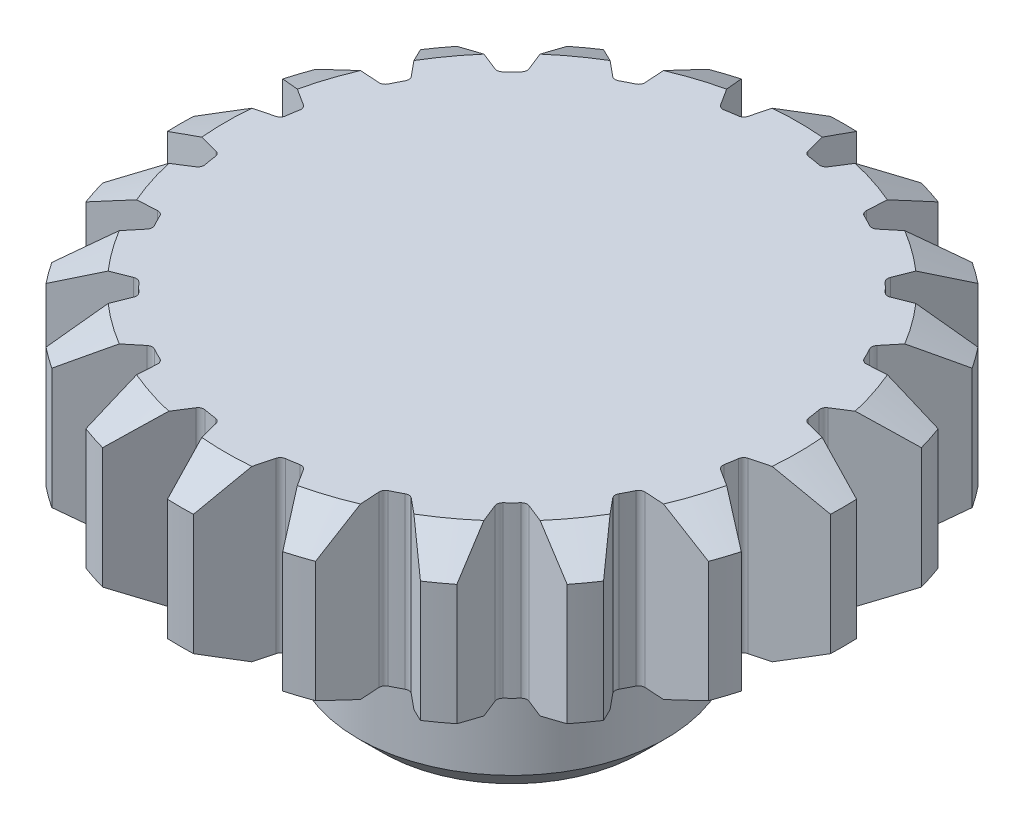
SolidWorks part; units mm, degrees
ref_plane "前视基准面" through (0, 0, 0) normal (0, 0, 1) x (1, 0, 0)
ref_plane "上视基准面" through (0, 0, 0) normal (0, 1, 0) x (1, 0, 0)
ref_plane "右视基准面" through (0, 0, 0) normal (1, 0, 0) x (0, 0, -1)
other "Configuration Table"
sketch "草图1" plane through (0, 0, 0) normal (0, 1, 0) x (1, 0, 0)
  line L0 (0.9745, 8.6442) -> (0.4232, 10.7717)
  line L1 (-0.4232, 10.7717) -> (-0.9745, 8.6442)
  line L2 (-1.7444, 8.5223) -> (-2.9261, 10.3753)
  line L3 (-3.7311, 10.1137) -> (-3.5981, 7.92)
  line L4 (-4.2925, 7.5661) -> (-5.989, 8.9632)
  line L5 (-6.6738, 8.4657) -> (-5.8694, 6.4205)
  line L6 (-6.4205, 5.8694) -> (-8.4657, 6.6738)
  line L7 (-8.9632, 5.989) -> (-7.5661, 4.2925)
  line L8 (-7.92, 3.5981) -> (-10.1137, 3.7311)
  line L9 (-10.3753, 2.9261) -> (-8.5223, 1.7444)
  line L10 (-8.6442, 0.9745) -> (-10.7717, 0.4232)
  line L11 (-10.7717, -0.4232) -> (-8.6442, -0.9745)
  line L12 (-8.5223, -1.7444) -> (-10.3753, -2.9261)
  line L13 (-10.1137, -3.7311) -> (-7.92, -3.5981)
  line L14 (-7.5661, -4.2925) -> (-8.9632, -5.989)
  line L15 (-8.4657, -6.6738) -> (-6.4205, -5.8694)
  line L16 (-5.8694, -6.4205) -> (-6.6738, -8.4657)
  line L17 (-5.989, -8.9632) -> (-4.2925, -7.5661)
  line L18 (-3.5981, -7.92) -> (-3.7311, -10.1137)
  line L19 (-2.9261, -10.3753) -> (-1.7444, -8.5223)
  line L20 (-0.9745, -8.6442) -> (-0.4232, -10.7717)
  line L21 (0.4232, -10.7717) -> (0.9745, -8.6442)
  line L22 (1.7444, -8.5223) -> (2.9261, -10.3753)
  line L23 (3.7311, -10.1137) -> (3.5981, -7.92)
  line L24 (4.2925, -7.5661) -> (5.989, -8.9632)
  line L25 (6.6738, -8.4657) -> (5.8694, -6.4205)
  line L26 (6.4205, -5.8694) -> (8.4657, -6.6738)
  line L27 (8.9632, -5.989) -> (7.5661, -4.2925)
  line L28 (7.92, -3.5981) -> (10.1137, -3.7311)
  line L29 (10.3753, -2.9261) -> (8.5223, -1.7444)
  line L30 (8.6442, -0.9745) -> (10.7717, -0.4232)
  line L31 (10.7717, 0.4232) -> (8.6442, 0.9745)
  line L32 (8.5223, 1.7444) -> (10.3753, 2.9261)
  line L33 (10.1137, 3.7311) -> (7.92, 3.5981)
  line L34 (7.5661, 4.2925) -> (8.9632, 5.989)
  line L35 (8.4657, 6.6738) -> (6.4205, 5.8694)
  line L36 (5.8694, 6.4205) -> (6.6738, 8.4657)
  line L37 (5.989, 8.9632) -> (4.2925, 7.5661)
  line L38 (3.5981, 7.92) -> (3.7311, 10.1137)
  line L39 (2.9261, 10.3753) -> (1.7444, 8.5223)
  arc A0 (0.4232, 10.7717) -> (-0.4232, 10.7717) centre (0, 0) ccw
  arc A1 (-1.1383, 8.4991) -> (-0.9745, 8.6442) centre (-1.1643, 8.6934) ccw
  arc A2 (-1.1383, 8.4991) -> (-1.5438, 8.4349) centre (0, 0) ccw
  arc A3 (-1.7444, 8.5223) -> (-1.5438, 8.4349) centre (-1.5791, 8.6277) ccw
  arc A4 (-2.9261, 10.3753) -> (-3.7311, 10.1137) centre (0, 0) ccw
  arc A5 (-3.7089, 7.7314) -> (-3.5981, 7.92) centre (-3.7937, 7.9081) ccw
  arc A6 (-3.7089, 7.7314) -> (-4.0748, 7.545) centre (0, 0) ccw
  arc A7 (-4.2925, 7.5661) -> (-4.0748, 7.545) centre (-4.1679, 7.7174) ccw
  arc A8 (-5.989, 8.9632) -> (-6.6738, 8.4657) centre (0, 0) ccw
  arc A9 (-5.9165, 6.2069) -> (-5.8694, 6.4205) centre (-6.0518, 6.3487) ccw
  arc A10 (-5.9165, 6.2069) -> (-6.2069, 5.9165) centre (0, 0) ccw
  arc A11 (-6.4205, 5.8694) -> (-6.2069, 5.9165) centre (-6.3487, 6.0518) ccw
  arc A12 (-8.4657, 6.6738) -> (-8.9632, 5.989) centre (0, 0) ccw
  arc A13 (-7.545, 4.0748) -> (-7.5661, 4.2925) centre (-7.7174, 4.1679) ccw
  arc A14 (-7.545, 4.0748) -> (-7.7314, 3.7089) centre (0, 0) ccw
  arc A15 (-7.92, 3.5981) -> (-7.7314, 3.7089) centre (-7.9081, 3.7937) ccw
  arc A16 (-10.1137, 3.7311) -> (-10.3753, 2.9261) centre (0, 0) ccw
  arc A17 (-8.4349, 1.5438) -> (-8.5223, 1.7444) centre (-8.6277, 1.5791) ccw
  arc A18 (-8.4349, 1.5438) -> (-8.4991, 1.1383) centre (0, 0) ccw
  arc A19 (-8.6442, 0.9745) -> (-8.4991, 1.1383) centre (-8.6934, 1.1643) ccw
  arc A20 (-10.7717, 0.4232) -> (-10.7717, -0.4232) centre (0, 0) ccw
  arc A21 (-8.4991, -1.1383) -> (-8.6442, -0.9745) centre (-8.6934, -1.1643) ccw
  arc A22 (-8.4991, -1.1383) -> (-8.4349, -1.5438) centre (0, 0) ccw
  arc A23 (-8.5223, -1.7444) -> (-8.4349, -1.5438) centre (-8.6277, -1.5791) ccw
  arc A24 (-10.3753, -2.9261) -> (-10.1137, -3.7311) centre (0, 0) ccw
  arc A25 (-7.7314, -3.7089) -> (-7.92, -3.5981) centre (-7.9081, -3.7937) ccw
  arc A26 (-7.7314, -3.7089) -> (-7.545, -4.0748) centre (0, 0) ccw
  arc A27 (-7.5661, -4.2925) -> (-7.545, -4.0748) centre (-7.7174, -4.1679) ccw
  arc A28 (-8.9632, -5.989) -> (-8.4657, -6.6738) centre (0, 0) ccw
  arc A29 (-6.2069, -5.9165) -> (-6.4205, -5.8694) centre (-6.3487, -6.0518) ccw
  arc A30 (-6.2069, -5.9165) -> (-5.9165, -6.2069) centre (0, 0) ccw
  arc A31 (-5.8694, -6.4205) -> (-5.9165, -6.2069) centre (-6.0518, -6.3487) ccw
  arc A32 (-6.6738, -8.4657) -> (-5.989, -8.9632) centre (0, 0) ccw
  arc A33 (-4.0748, -7.545) -> (-4.2925, -7.5661) centre (-4.1679, -7.7174) ccw
  arc A34 (-4.0748, -7.545) -> (-3.7089, -7.7314) centre (0, 0) ccw
  arc A35 (-3.5981, -7.92) -> (-3.7089, -7.7314) centre (-3.7937, -7.9081) ccw
  arc A36 (-3.7311, -10.1137) -> (-2.9261, -10.3753) centre (0, 0) ccw
  arc A37 (-1.5438, -8.4349) -> (-1.7444, -8.5223) centre (-1.5791, -8.6277) ccw
  arc A38 (-1.5438, -8.4349) -> (-1.1383, -8.4991) centre (0, 0) ccw
  arc A39 (-0.9745, -8.6442) -> (-1.1383, -8.4991) centre (-1.1643, -8.6934) ccw
  arc A40 (-0.4232, -10.7717) -> (0.4232, -10.7717) centre (0, 0) ccw
  arc A41 (1.1383, -8.4991) -> (0.9745, -8.6442) centre (1.1643, -8.6934) ccw
  arc A42 (1.1383, -8.4991) -> (1.5438, -8.4349) centre (0, 0) ccw
  arc A43 (1.7444, -8.5223) -> (1.5438, -8.4349) centre (1.5791, -8.6277) ccw
  arc A44 (2.9261, -10.3753) -> (3.7311, -10.1137) centre (0, 0) ccw
  arc A45 (3.7089, -7.7314) -> (3.5981, -7.92) centre (3.7937, -7.9081) ccw
  arc A46 (3.7089, -7.7314) -> (4.0748, -7.545) centre (0, 0) ccw
  arc A47 (4.2925, -7.5661) -> (4.0748, -7.545) centre (4.1679, -7.7174) ccw
  arc A48 (5.989, -8.9632) -> (6.6738, -8.4657) centre (0, 0) ccw
  arc A49 (5.9165, -6.2069) -> (5.8694, -6.4205) centre (6.0518, -6.3487) ccw
  arc A50 (5.9165, -6.2069) -> (6.2069, -5.9165) centre (0, 0) ccw
  arc A51 (6.4205, -5.8694) -> (6.2069, -5.9165) centre (6.3487, -6.0518) ccw
  arc A52 (8.4657, -6.6738) -> (8.9632, -5.989) centre (0, 0) ccw
  arc A53 (7.545, -4.0748) -> (7.5661, -4.2925) centre (7.7174, -4.1679) ccw
  arc A54 (7.545, -4.0748) -> (7.7314, -3.7089) centre (0, 0) ccw
  arc A55 (7.92, -3.5981) -> (7.7314, -3.7089) centre (7.9081, -3.7937) ccw
  arc A56 (10.1137, -3.7311) -> (10.3753, -2.9261) centre (0, 0) ccw
  arc A57 (8.4349, -1.5438) -> (8.5223, -1.7444) centre (8.6277, -1.5791) ccw
  arc A58 (8.4349, -1.5438) -> (8.4991, -1.1383) centre (0, 0) ccw
  arc A59 (8.6442, -0.9745) -> (8.4991, -1.1383) centre (8.6934, -1.1643) ccw
  arc A60 (10.7717, -0.4232) -> (10.7717, 0.4232) centre (0, 0) ccw
  arc A61 (8.4991, 1.1383) -> (8.6442, 0.9745) centre (8.6934, 1.1643) ccw
  arc A62 (8.4991, 1.1383) -> (8.4349, 1.5438) centre (0, 0) ccw
  arc A63 (8.5223, 1.7444) -> (8.4349, 1.5438) centre (8.6277, 1.5791) ccw
  arc A64 (10.3753, 2.9261) -> (10.1137, 3.7311) centre (0, 0) ccw
  arc A65 (7.7314, 3.7089) -> (7.92, 3.5981) centre (7.9081, 3.7937) ccw
  arc A66 (7.7314, 3.7089) -> (7.545, 4.0748) centre (0, 0) ccw
  arc A67 (7.5661, 4.2925) -> (7.545, 4.0748) centre (7.7174, 4.1679) ccw
  arc A68 (8.9632, 5.989) -> (8.4657, 6.6738) centre (0, 0) ccw
  arc A69 (6.2069, 5.9165) -> (6.4205, 5.8694) centre (6.3487, 6.0518) ccw
  arc A70 (6.2069, 5.9165) -> (5.9165, 6.2069) centre (0, 0) ccw
  arc A71 (5.8694, 6.4205) -> (5.9165, 6.2069) centre (6.0518, 6.3487) ccw
  arc A72 (6.6738, 8.4657) -> (5.989, 8.9632) centre (0, 0) ccw
  arc A73 (4.0748, 7.545) -> (4.2925, 7.5661) centre (4.1679, 7.7174) ccw
  arc A74 (4.0748, 7.545) -> (3.7089, 7.7314) centre (0, 0) ccw
  arc A75 (3.5981, 7.92) -> (3.7089, 7.7314) centre (3.7937, 7.9081) ccw
  arc A76 (3.7311, 10.1137) -> (2.9261, 10.3753) centre (0, 0) ccw
  arc A77 (1.5438, 8.4349) -> (1.7444, 8.5223) centre (1.5791, 8.6277) ccw
  arc A78 (1.5438, 8.4349) -> (1.1383, 8.4991) centre (0, 0) ccw
  arc A79 (0.9745, 8.6442) -> (1.1383, 8.4991) centre (1.1643, 8.6934) ccw
extrude "凸台-拉伸1" add sketch "草图1" along normal blind 5.5
sketch "草图3" plane through (0, 0, 0) normal (0, -1, 0) x (1, 0, 0)
  arc A0 (-0.7265, 3.1784) -> (-0.8949, 3.1351) centre (-0.0001, -0.0002) ccw
  arc A1 (-0.99, 2.5302) -> (-1.0107, 2.522) centre (-0.0002, -0.0001) ccw
  arc A2 (-1.4941, 2.8979) -> (-1.6465, 2.8141) centre (-0.0001, -0.0002) ccw
  arc A3 (-1.5881, 2.2045) -> (-1.6062, 2.1914) centre (-0.0002, -0.0001) ccw
  arc A4 (-2.1679, 2.4353) -> (-2.2946, 2.3163) centre (0, -0.0002) ccw
  arc A5 (-2.0865, 1.7404) -> (-2.1007, 1.7232) centre (-0.0002, -0.0001) ccw
  arc A6 (-2.7054, 1.8197) -> (-2.7986, 1.6729) centre (0, -0.0002) ccw
  arc A7 (-2.4538, 1.1669) -> (-2.4633, 1.1467) centre (-0.0002, -0.0001) ccw
  arc A8 (-3.073, 1.0897) -> (-3.1267, 0.9244) centre (0, -0.0001) ccw
  arc A9 (-2.6669, 0.52) -> (-2.6711, 0.4981) centre (-0.0002, -0.0001) ccw
  arc A10 (-3.2475, 0.2913) -> (-3.2584, 0.1178) centre (0, -0.0001) ccw
  arc A11 (-2.7124, -0.1595) -> (-2.711, -0.1818) centre (-0.0002, -0.0001) ccw
  arc A12 (-3.2179, -0.5254) -> (-3.1853, -0.6961) centre (0, 0) ccw
  arc A13 (-2.5876, -0.829) -> (-2.5807, -0.8502) centre (-0.0002, -0.0001) ccw
  arc A14 (-2.9862, -1.3091) -> (-2.9122, -1.4664) centre (0, 0) ccw
  arc A15 (-2.3001, -1.4464) -> (-2.2882, -1.4653) centre (-0.0002, -0.0001) ccw
  arc A16 (-2.5668, -2.0106) -> (-2.456, -2.1445) centre (0, 0.0001) ccw
  arc A17 (-1.8682, -1.973) -> (-1.8519, -1.9883) centre (-0.0002, -0.0001) ccw
  arc A18 (-1.9862, -2.5857) -> (-1.8456, -2.6879) centre (0, 0.0001) ccw
  arc A19 (-1.3188, -2.3756) -> (-1.2993, -2.3863) centre (-0.0002, -0.0001) ccw
  arc A20 (-1.2808, -2.9984) -> (-1.1191, -3.0624) centre (-0.0001, 0.0001) ccw
  arc A21 (-0.6866, -2.6289) -> (-0.665, -2.6344) centre (-0.0002, -0.0001) ccw
  arc A22 (-0.4949, -3.2227) -> (-0.3224, -3.2444) centre (-0.0001, 0.0001) ccw
  arc A23 (-0.0114, -2.717) -> (0.011, -2.717) centre (-0.0002, -0.0001) ccw
  arc A24 (0.3221, -3.2444) -> (0.4945, -3.2227) centre (-0.0002, 0.0001) ccw
  arc A25 (0.6647, -2.6344) -> (0.6863, -2.6289) centre (-0.0002, -0.0001) ccw
  arc A26 (1.1188, -3.0624) -> (1.2804, -2.9984) centre (-0.0002, 0.0001) ccw
  arc A27 (1.299, -2.3863) -> (1.3185, -2.3756) centre (-0.0002, -0.0001) ccw
  arc A28 (1.8452, -2.6879) -> (1.9859, -2.5857) centre (-0.0003, 0.0001) ccw
  arc A29 (1.8516, -1.9883) -> (1.8678, -1.973) centre (-0.0002, -0.0001) ccw
  arc A30 (2.4557, -2.1445) -> (2.5665, -2.0106) centre (-0.0003, 0.0001) ccw
  arc A31 (2.2878, -1.4653) -> (2.2998, -1.4464) centre (-0.0002, -0.0001) ccw
  arc A32 (2.9118, -1.4664) -> (2.9858, -1.3091) centre (-0.0003, 0) ccw
  arc A33 (2.5803, -0.8502) -> (2.5872, -0.829) centre (-0.0002, -0.0001) ccw
  arc A34 (3.185, -0.6961) -> (3.2176, -0.5254) centre (-0.0004, 0) ccw
  arc A35 (2.7107, -0.1818) -> (2.7121, -0.1595) centre (-0.0002, -0.0001) ccw
  arc A36 (3.2581, 0.1178) -> (3.2471, 0.2913) centre (-0.0004, -0.0001) ccw
  arc A37 (2.6707, 0.4981) -> (2.6666, 0.52) centre (-0.0002, -0.0001) ccw
  arc A38 (3.1264, 0.9244) -> (3.0727, 1.0897) centre (-0.0003, -0.0001) ccw
  arc A39 (2.4629, 1.1467) -> (2.4534, 1.1669) centre (-0.0002, -0.0001) ccw
  arc A40 (2.7982, 1.6729) -> (2.7051, 1.8197) centre (-0.0003, -0.0002) ccw
  arc A41 (2.1004, 1.7232) -> (2.0862, 1.7404) centre (-0.0002, -0.0001) ccw
  arc A42 (2.2943, 2.3163) -> (2.1676, 2.4353) centre (-0.0003, -0.0002) ccw
  arc A43 (1.6058, 2.1914) -> (1.5878, 2.2045) centre (-0.0002, -0.0001) ccw
  arc A44 (1.6461, 2.8141) -> (1.4938, 2.8979) centre (-0.0003, -0.0002) ccw
  arc A45 (1.0104, 2.522) -> (0.9896, 2.5302) centre (-0.0002, -0.0001) ccw
  arc A46 (0.8945, 3.1351) -> (0.7262, 3.1784) centre (-0.0002, -0.0002) ccw
  arc A47 (0.3514, 2.6941) -> (0.3293, 2.6969) centre (-0.0002, -0.0001) ccw
  arc A48 (0.0867, 3.2591) -> (-0.0871, 3.2591) centre (-0.0002, -0.0003) ccw
  arc A49 (-0.3296, 2.6969) -> (-0.3518, 2.6941) centre (-0.0002, -0.0001) ccw
  circle A51 centre (0, -0.0001) radius 5
  spline S0 degree 3 poles (-0.3518, 2.6941) (-0.3605, 2.6929) (-0.3784, 2.6931) (-0.4128, 2.7028) (-0.4491, 2.7298) (-0.4793, 2.7741) (-0.4985, 2.8237) (-0.5171, 2.8734) (-0.5482, 2.937) (-0.6123, 3.0431) (-0.6788, 3.1261) (-0.7265, 3.1784) knots 0 0 0 0 0.041734 0.083468 0.166936 0.250403 0.333871 0.417137 0.500403 0.666936 1 1 1 1 weights 1 1 1 1 1 1 1 1 1 1 1 1
  spline S1 degree 3 poles (-0.8949, 3.1351) (-0.9115, 3.0664) (-0.9298, 2.9616) (-0.9349, 2.8377) (-0.9315, 2.7671) (-0.9238, 2.7145) (-0.9168, 2.6618) (-0.9219, 2.6084) (-0.9407, 2.5673) (-0.9661, 2.5422) (-0.9817, 2.5334) (-0.99, 2.5302) knots 0 0 0 0 0.333125 0.499688 0.582969 0.66625 0.749687 0.833125 0.916562 0.958281 1 1 1 1 weights 1 1 1 1 1 1 1 1 1 1 1 1
  spline S2 degree 3 poles (-1.0107, 2.522) (-1.0189, 2.5187) (-1.0363, 2.5144) (-1.072, 2.5153) (-1.1139, 2.5324) (-1.1541, 2.5678) (-1.1851, 2.6111) (-1.2155, 2.6546) (-1.2614, 2.7085) (-1.3499, 2.7953) (-1.4349, 2.8591) (-1.4941, 2.8979) knots 0 0 0 0 0.041734 0.083468 0.166936 0.250403 0.333871 0.417137 0.500403 0.666936 1 1 1 1 weights 1 1 1 1 1 1 1 1 1 1 1 1
  spline S3 degree 3 poles (-1.6465, 2.8141) (-1.6455, 2.7434) (-1.6371, 2.6373) (-1.6112, 2.5161) (-1.5904, 2.4485) (-1.5699, 2.3995) (-1.55, 2.3502) (-1.5417, 2.2973) (-1.5496, 2.2527) (-1.568, 2.2221) (-1.5809, 2.2097) (-1.5881, 2.2045) knots 0 0 0 0 0.333125 0.499688 0.582969 0.66625 0.749687 0.833125 0.916562 0.958281 1 1 1 1 weights 1 1 1 1 1 1 1 1 1 1 1 1
  spline S4 degree 3 poles (-1.6062, 2.1914) (-1.6133, 2.1862) (-1.629, 2.1777) (-1.6639, 2.1697) (-1.7087, 2.1759) (-1.7565, 2.2002) (-1.7972, 2.2344) (-1.8375, 2.269) (-1.8954, 2.3097) (-2.0026, 2.3718) (-2.1009, 2.4125) (-2.1679, 2.4353) knots 0 0 0 0 0.041734 0.083468 0.166936 0.250403 0.333871 0.417137 0.500403 0.666936 1 1 1 1 weights 1 1 1 1 1 1 1 1 1 1 1 1
  spline S5 degree 3 poles (-2.2946, 2.3163) (-2.2761, 2.248) (-2.2416, 2.1474) (-2.1864, 2.0364) (-2.1493, 1.9761) (-2.1174, 1.9338) (-2.0858, 1.8909) (-2.0645, 1.8417) (-2.0612, 1.7966) (-2.0714, 1.7624) (-2.0808, 1.7472) (-2.0865, 1.7404) knots 0 0 0 0 0.333125 0.499688 0.582969 0.66625 0.749687 0.833125 0.916562 0.958281 1 1 1 1 weights 1 1 1 1 1 1 1 1 1 1 1 1
  spline S6 degree 3 poles (-2.1007, 1.7232) (-2.1063, 1.7163) (-2.1195, 1.7042) (-2.1512, 1.6878) (-2.1962, 1.6826) (-2.2485, 1.6943) (-2.2965, 1.7173) (-2.3441, 1.7407) (-2.4102, 1.7658) (-2.5296, 1.7993) (-2.6349, 1.8143) (-2.7054, 1.8197) knots 0 0 0 0 0.041734 0.083468 0.166936 0.250403 0.333871 0.417137 0.500403 0.666936 1 1 1 1 weights 1 1 1 1 1 1 1 1 1 1 1 1
  spline S7 degree 3 poles (-2.7986, 1.6729) (-2.7636, 1.6114) (-2.7052, 1.5225) (-2.6241, 1.4288) (-2.5733, 1.3796) (-2.5318, 1.3465) (-2.4905, 1.3129) (-2.4577, 1.2705) (-2.4432, 1.2276) (-2.4446, 1.1919) (-2.45, 1.1749) (-2.4538, 1.1669) knots 0 0 0 0 0.333125 0.499688 0.582969 0.66625 0.749687 0.833125 0.916562 0.958281 1 1 1 1 weights 1 1 1 1 1 1 1 1 1 1 1 1
  spline S8 degree 3 poles (-2.4633, 1.1467) (-2.467, 1.1386) (-2.4767, 1.1236) (-2.5034, 1.0998) (-2.5456, 1.0837) (-2.5992, 1.0819) (-2.6514, 1.0922) (-2.7034, 1.1032) (-2.7737, 1.111) (-2.8976, 1.1137) (-3.0033, 1.102) (-3.073, 1.0897) knots 0 0 0 0 0.041734 0.083468 0.166936 0.250403 0.333871 0.417137 0.500403 0.666936 1 1 1 1 weights 1 1 1 1 1 1 1 1 1 1 1 1
  spline S9 degree 3 poles (-3.1267, 0.9244) (-3.0776, 0.8736) (-2.9989, 0.8019) (-2.897, 0.7313) (-2.8355, 0.6963) (-2.7871, 0.6746) (-2.7388, 0.6523) (-2.6965, 0.6194) (-2.6718, 0.5815) (-2.6642, 0.5466) (-2.6652, 0.5287) (-2.6669, 0.52) knots 0 0 0 0 0.333125 0.499688 0.582969 0.66625 0.749687 0.833125 0.916562 0.958281 1 1 1 1 weights 1 1 1 1 1 1 1 1 1 1 1 1
  spline S10 degree 3 poles (-2.6711, 0.4981) (-2.6727, 0.4894) (-2.6784, 0.4724) (-2.6983, 0.4427) (-2.7352, 0.4166) (-2.7866, 0.4016) (-2.8398, 0.3986) (-2.8928, 0.3962) (-2.9628, 0.3863) (-3.0835, 0.3582) (-3.1831, 0.3205) (-3.2475, 0.2913) knots 0 0 0 0 0.041734 0.083468 0.166936 0.250403 0.333871 0.417137 0.500403 0.666936 1 1 1 1 weights 1 1 1 1 1 1 1 1 1 1 1 1
  spline S11 degree 3 poles (-3.2584, 0.1178) (-3.1981, 0.0808) (-3.1041, 0.031) (-2.9879, -0.0121) (-2.9196, -0.0307) (-2.8673, -0.0397) (-2.815, -0.0493) (-2.7658, -0.0706) (-2.7325, -0.1012) (-2.7165, -0.1331) (-2.713, -0.1507) (-2.7124, -0.1595) knots 0 0 0 0 0.333125 0.499688 0.582969 0.66625 0.749687 0.833125 0.916562 0.958281 1 1 1 1 weights 1 1 1 1 1 1 1 1 1 1 1 1
  spline S12 degree 3 poles (-2.711, -0.1818) (-2.7105, -0.1906) (-2.7117, -0.2085) (-2.7236, -0.2422) (-2.7529, -0.2767) (-2.799, -0.304) (-2.8497, -0.3201) (-2.9005, -0.3356) (-2.9659, -0.3626) (-3.0758, -0.4199) (-3.1628, -0.4811) (-3.2179, -0.5254) knots 0 0 0 0 0.041734 0.083468 0.166936 0.250403 0.333871 0.417137 0.500403 0.666936 1 1 1 1 weights 1 1 1 1 1 1 1 1 1 1 1 1
  spline S13 degree 3 poles (-3.1853, -0.6961) (-3.1178, -0.7171) (-3.0143, -0.7419) (-2.8911, -0.7547) (-2.8203, -0.7558) (-2.7674, -0.7515) (-2.7143, -0.7477) (-2.6614, -0.7562) (-2.6215, -0.7775) (-2.598, -0.8045) (-2.5903, -0.8206) (-2.5876, -0.829) knots 0 0 0 0 0.333125 0.499688 0.582969 0.66625 0.749687 0.833125 0.916562 0.958281 1 1 1 1 weights 1 1 1 1 1 1 1 1 1 1 1 1
  spline S14 degree 3 poles (-2.5807, -0.8502) (-2.5779, -0.8587) (-2.5747, -0.8762) (-2.5778, -0.9119) (-2.5976, -0.9526) (-2.6354, -0.9905) (-2.6806, -1.0187) (-2.7259, -1.0463) (-2.7825, -1.0887) (-2.8747, -1.1716) (-2.9438, -1.2525) (-2.9862, -1.3091) knots 0 0 0 0 0.041734 0.083468 0.166936 0.250403 0.333871 0.417137 0.500403 0.666936 1 1 1 1 weights 1 1 1 1 1 1 1 1 1 1 1 1
  spline S15 degree 3 poles (-2.9122, -1.4664) (-2.8415, -1.4699) (-2.7351, -1.4682) (-2.6126, -1.45) (-2.5438, -1.4334) (-2.4936, -1.416) (-2.4431, -1.3992) (-2.3897, -1.3943) (-2.3458, -1.405) (-2.3164, -1.4253) (-2.3048, -1.439) (-2.3001, -1.4464) knots 0 0 0 0 0.333125 0.499688 0.582969 0.66625 0.749687 0.833125 0.916562 0.958281 1 1 1 1 weights 1 1 1 1 1 1 1 1 1 1 1 1
  spline S16 degree 3 poles (-2.2882, -1.4653) (-2.2834, -1.4727) (-2.2759, -1.489) (-2.2701, -1.5243) (-2.2791, -1.5686) (-2.3063, -1.6148) (-2.343, -1.6533) (-2.3801, -1.6913) (-2.4244, -1.7465) (-2.4931, -1.8496) (-2.5399, -1.9452) (-2.5668, -2.0106) knots 0 0 0 0 0.041734 0.083468 0.166936 0.250403 0.333871 0.417137 0.500403 0.666936 1 1 1 1 weights 1 1 1 1 1 1 1 1 1 1 1 1
  spline S17 degree 3 poles (-2.456, -2.1445) (-2.3867, -2.1303) (-2.2841, -2.1022) (-2.1699, -2.0541) (-2.1074, -2.0209) (-2.0631, -1.9916) (-2.0184, -1.9628) (-1.9679, -1.9447) (-1.9227, -1.9442) (-1.8891, -1.9565) (-1.8746, -1.9669) (-1.8682, -1.973) knots 0 0 0 0 0.333125 0.499688 0.582969 0.66625 0.749687 0.833125 0.916562 0.958281 1 1 1 1 weights 1 1 1 1 1 1 1 1 1 1 1 1
  spline S18 degree 3 poles (-1.8519, -1.9883) (-1.8454, -1.9943) (-1.8341, -2.0082) (-1.8197, -2.0409) (-1.8174, -2.0861) (-1.8323, -2.1375) (-1.8583, -2.184) (-1.8847, -2.23) (-1.9139, -2.2945) (-1.9548, -2.4115) (-1.9763, -2.5157) (-1.9862, -2.5857) knots 0 0 0 0 0.041734 0.083468 0.166936 0.250403 0.333871 0.417137 0.500403 0.666936 1 1 1 1 weights 1 1 1 1 1 1 1 1 1 1 1 1
  spline S19 degree 3 poles (-1.8456, -2.6879) (-1.782, -2.6569) (-1.6896, -2.6042) (-1.5909, -2.5291) (-1.5386, -2.4815) (-1.503, -2.4421) (-1.4669, -2.4031) (-1.4225, -2.373) (-1.3788, -2.3612) (-1.3433, -2.3648) (-1.3266, -2.3713) (-1.3188, -2.3756) knots 0 0 0 0 0.333125 0.499688 0.582969 0.66625 0.749687 0.833125 0.916562 0.958281 1 1 1 1 weights 1 1 1 1 1 1 1 1 1 1 1 1
  spline S20 degree 3 poles (-1.2993, -2.3863) (-1.2915, -2.3905) (-1.2771, -2.4012) (-1.255, -2.4293) (-1.2416, -2.4725) (-1.2432, -2.526) (-1.2568, -2.5775) (-1.2709, -2.6286) (-1.2832, -2.6983) (-1.2937, -2.8218) (-1.2886, -2.9281) (-1.2808, -2.9984) knots 0 0 0 0 0.041734 0.083468 0.166936 0.250403 0.333871 0.417137 0.500403 0.666936 1 1 1 1 weights 1 1 1 1 1 1 1 1 1 1 1 1
  spline S21 degree 3 poles (-1.1191, -3.0624) (-1.0653, -3.0165) (-0.9889, -2.9425) (-0.912, -2.8453) (-0.8732, -2.7861) (-0.8485, -2.7391) (-0.8232, -2.6923) (-0.7877, -2.6522) (-0.7483, -2.6299) (-0.713, -2.6245) (-0.6952, -2.6266) (-0.6866, -2.6289) knots 0 0 0 0 0.333125 0.499688 0.582969 0.66625 0.749687 0.833125 0.916562 0.958281 1 1 1 1 weights 1 1 1 1 1 1 1 1 1 1 1 1
  spline S22 degree 3 poles (-0.665, -2.6344) (-0.6564, -2.6366) (-0.6399, -2.6433) (-0.6115, -2.665) (-0.5877, -2.7035) (-0.576, -2.7558) (-0.5763, -2.809) (-0.5773, -2.8621) (-0.5718, -2.9326) (-0.5513, -3.0549) (-0.52, -3.1565) (-0.4949, -3.2227) knots 0 0 0 0 0.041734 0.083468 0.166936 0.250403 0.333871 0.417137 0.500403 0.666936 1 1 1 1 weights 1 1 1 1 1 1 1 1 1 1 1 1
  spline S23 degree 3 poles (-0.3224, -3.2444) (-0.2817, -3.1867) (-0.226, -3.0959) (-0.1758, -2.9827) (-0.1529, -2.9157) (-0.1407, -2.8641) (-0.1278, -2.8124) (-0.1034, -2.7647) (-0.0708, -2.7333) (-0.0379, -2.7193) (-0.0202, -2.717) (-0.0114, -2.717) knots 0 0 0 0 0.333125 0.499688 0.582969 0.66625 0.749687 0.833125 0.916562 0.958281 1 1 1 1 weights 1 1 1 1 1 1 1 1 1 1 1 1
  spline S24 degree 3 poles (0.011, -2.717) (0.0199, -2.717) (0.0376, -2.7193) (0.0705, -2.7333) (0.1031, -2.7647) (0.1275, -2.8124) (0.1403, -2.864) (0.1526, -2.9157) (0.1754, -2.9827) (0.2257, -3.0959) (0.2813, -3.1867) (0.3221, -3.2444) knots 0 0 0 0 0.041734 0.083468 0.166936 0.250403 0.333871 0.417137 0.500403 0.666936 1 1 1 1 weights 1 1 1 1 1 1 1 1 1 1 1 1
  spline S25 degree 3 poles (0.4945, -3.2227) (0.5197, -3.1565) (0.551, -3.0549) (0.5715, -2.9326) (0.577, -2.8621) (0.576, -2.809) (0.5756, -2.7558) (0.5874, -2.7035) (0.6111, -2.665) (0.6395, -2.6433) (0.6561, -2.6366) (0.6647, -2.6344) knots 0 0 0 0 0.333125 0.499688 0.582969 0.66625 0.749687 0.833125 0.916562 0.958281 1 1 1 1 weights 1 1 1 1 1 1 1 1 1 1 1 1
  spline S26 degree 3 poles (0.6863, -2.6289) (0.6949, -2.6266) (0.7126, -2.6245) (0.748, -2.6299) (0.7874, -2.6522) (0.8229, -2.6923) (0.8482, -2.7391) (0.8729, -2.7861) (0.9117, -2.8453) (0.9885, -2.9425) (1.065, -3.0165) (1.1188, -3.0624) knots 0 0 0 0 0.041734 0.083468 0.166936 0.250403 0.333871 0.417137 0.500403 0.666936 1 1 1 1 weights 1 1 1 1 1 1 1 1 1 1 1 1
  spline S27 degree 3 poles (1.2804, -2.9984) (1.2883, -2.9281) (1.2934, -2.8218) (1.2828, -2.6983) (1.2706, -2.6286) (1.2565, -2.5775) (1.2429, -2.526) (1.2412, -2.4725) (1.2547, -2.4293) (1.2768, -2.4012) (1.2912, -2.3905) (1.299, -2.3863) knots 0 0 0 0 0.333125 0.499688 0.582969 0.66625 0.749687 0.833125 0.916562 0.958281 1 1 1 1 weights 1 1 1 1 1 1 1 1 1 1 1 1
  spline S28 degree 3 poles (1.3185, -2.3756) (1.3263, -2.3713) (1.3429, -2.3648) (1.3785, -2.3612) (1.4222, -2.373) (1.4665, -2.4031) (1.5027, -2.4421) (1.5383, -2.4815) (1.5906, -2.5291) (1.6892, -2.6042) (1.7817, -2.6569) (1.8452, -2.6879) knots 0 0 0 0 0.041734 0.083468 0.166936 0.250403 0.333871 0.417137 0.500403 0.666936 1 1 1 1 weights 1 1 1 1 1 1 1 1 1 1 1 1
  spline S29 degree 3 poles (1.9859, -2.5857) (1.976, -2.5157) (1.9545, -2.4115) (1.9136, -2.2945) (1.8844, -2.23) (1.858, -2.184) (1.832, -2.1375) (1.8171, -2.0861) (1.8194, -2.0409) (1.8338, -2.0082) (1.8451, -1.9943) (1.8516, -1.9883) knots 0 0 0 0 0.333125 0.499688 0.582969 0.66625 0.749687 0.833125 0.916562 0.958281 1 1 1 1 weights 1 1 1 1 1 1 1 1 1 1 1 1
  spline S30 degree 3 poles (1.8678, -1.973) (1.8743, -1.9669) (1.8888, -1.9565) (1.9224, -1.9442) (1.9676, -1.9447) (2.0181, -1.9628) (2.0628, -1.9916) (2.1071, -2.0209) (2.1696, -2.0541) (2.2838, -2.1022) (2.3864, -2.1303) (2.4557, -2.1445) knots 0 0 0 0 0.041734 0.083468 0.166936 0.250403 0.333871 0.417137 0.500403 0.666936 1 1 1 1 weights 1 1 1 1 1 1 1 1 1 1 1 1
  spline S31 degree 3 poles (2.5665, -2.0106) (2.5395, -1.9452) (2.4927, -1.8496) (2.424, -1.7465) (2.3797, -1.6913) (2.3427, -1.6533) (2.306, -1.6148) (2.2788, -1.5686) (2.2698, -1.5243) (2.2756, -1.489) (2.2831, -1.4727) (2.2878, -1.4653) knots 0 0 0 0 0.333125 0.499688 0.582969 0.66625 0.749687 0.833125 0.916562 0.958281 1 1 1 1 weights 1 1 1 1 1 1 1 1 1 1 1 1
  spline S32 degree 3 poles (2.2998, -1.4464) (2.3045, -1.439) (2.316, -1.4253) (2.3455, -1.405) (2.3894, -1.3943) (2.4428, -1.3992) (2.4933, -1.416) (2.5434, -1.4334) (2.6122, -1.45) (2.7348, -1.4682) (2.8412, -1.4699) (2.9118, -1.4664) knots 0 0 0 0 0.041734 0.083468 0.166936 0.250403 0.333871 0.417137 0.500403 0.666936 1 1 1 1 weights 1 1 1 1 1 1 1 1 1 1 1 1
  spline S33 degree 3 poles (2.9858, -1.3091) (2.9435, -1.2525) (2.8744, -1.1716) (2.7822, -1.0887) (2.7256, -1.0463) (2.6802, -1.0187) (2.6351, -0.9905) (2.5973, -0.9526) (2.5775, -0.9119) (2.5744, -0.8762) (2.5776, -0.8587) (2.5803, -0.8502) knots 0 0 0 0 0.333125 0.499688 0.582969 0.66625 0.749687 0.833125 0.916562 0.958281 1 1 1 1 weights 1 1 1 1 1 1 1 1 1 1 1 1
  spline S34 degree 3 poles (2.5872, -0.829) (2.59, -0.8206) (2.5977, -0.8045) (2.6212, -0.7775) (2.6611, -0.7562) (2.714, -0.7477) (2.7671, -0.7515) (2.82, -0.7558) (2.8907, -0.7547) (3.014, -0.7419) (3.1175, -0.7171) (3.185, -0.6961) knots 0 0 0 0 0.041734 0.083468 0.166936 0.250403 0.333871 0.417137 0.500403 0.666936 1 1 1 1 weights 1 1 1 1 1 1 1 1 1 1 1 1
  spline S35 degree 3 poles (3.2176, -0.5254) (3.1625, -0.4811) (3.0754, -0.4199) (2.9655, -0.3626) (2.9001, -0.3356) (2.8494, -0.3201) (2.7986, -0.304) (2.7525, -0.2767) (2.7233, -0.2422) (2.7114, -0.2085) (2.7101, -0.1906) (2.7107, -0.1818) knots 0 0 0 0 0.333125 0.499688 0.582969 0.66625 0.749687 0.833125 0.916562 0.958281 1 1 1 1 weights 1 1 1 1 1 1 1 1 1 1 1 1
  spline S36 degree 3 poles (2.7121, -0.1595) (2.7126, -0.1507) (2.7161, -0.1331) (2.7321, -0.1012) (2.7655, -0.0706) (2.8147, -0.0493) (2.867, -0.0397) (2.9193, -0.0307) (2.9876, -0.0121) (3.1038, 0.031) (3.1978, 0.0808) (3.2581, 0.1178) knots 0 0 0 0 0.041734 0.083468 0.166936 0.250403 0.333871 0.417137 0.500403 0.666936 1 1 1 1 weights 1 1 1 1 1 1 1 1 1 1 1 1
  spline S37 degree 3 poles (3.2471, 0.2913) (3.1827, 0.3205) (3.0832, 0.3582) (2.9625, 0.3863) (2.8925, 0.3962) (2.8394, 0.3986) (2.7863, 0.4016) (2.7349, 0.4166) (2.6979, 0.4427) (2.678, 0.4724) (2.6724, 0.4894) (2.6707, 0.4981) knots 0 0 0 0 0.333125 0.499688 0.582969 0.66625 0.749687 0.833125 0.916562 0.958281 1 1 1 1 weights 1 1 1 1 1 1 1 1 1 1 1 1
  spline S38 degree 3 poles (2.6666, 0.52) (2.6649, 0.5287) (2.6639, 0.5466) (2.6715, 0.5815) (2.6962, 0.6194) (2.7385, 0.6523) (2.7868, 0.6746) (2.8352, 0.6963) (2.8967, 0.7313) (2.9986, 0.8019) (3.0772, 0.8736) (3.1264, 0.9244) knots 0 0 0 0 0.041734 0.083468 0.166936 0.250403 0.333871 0.417137 0.500403 0.666936 1 1 1 1 weights 1 1 1 1 1 1 1 1 1 1 1 1
  spline S39 degree 3 poles (3.0727, 1.0897) (3.003, 1.102) (2.8973, 1.1137) (2.7733, 1.111) (2.703, 1.1032) (2.6511, 1.0923) (2.5989, 1.0819) (2.5453, 1.0837) (2.5031, 1.0998) (2.4764, 1.1236) (2.4667, 1.1386) (2.4629, 1.1467) knots 0 0 0 0 0.333125 0.499688 0.582969 0.66625 0.749687 0.833125 0.916562 0.958281 1 1 1 1 weights 1 1 1 1 1 1 1 1 1 1 1 1
  spline S40 degree 3 poles (2.4534, 1.1669) (2.4496, 1.1749) (2.4443, 1.1919) (2.4429, 1.2276) (2.4574, 1.2705) (2.4902, 1.3129) (2.5314, 1.3465) (2.573, 1.3796) (2.6238, 1.4288) (2.7049, 1.5225) (2.7633, 1.6114) (2.7982, 1.6729) knots 0 0 0 0 0.041734 0.083468 0.166936 0.250403 0.333871 0.417137 0.500403 0.666936 1 1 1 1 weights 1 1 1 1 1 1 1 1 1 1 1 1
  spline S41 degree 3 poles (2.7051, 1.8197) (2.6346, 1.8143) (2.5292, 1.7993) (2.4099, 1.7658) (2.3437, 1.7407) (2.2961, 1.7173) (2.2481, 1.6943) (2.1958, 1.6826) (2.1509, 1.6878) (2.1191, 1.7042) (2.106, 1.7163) (2.1004, 1.7232) knots 0 0 0 0 0.333125 0.499688 0.582969 0.66625 0.749687 0.833125 0.916562 0.958281 1 1 1 1 weights 1 1 1 1 1 1 1 1 1 1 1 1
  spline S42 degree 3 poles (2.0862, 1.7404) (2.0805, 1.7472) (2.071, 1.7624) (2.0608, 1.7966) (2.0642, 1.8417) (2.0854, 1.8909) (2.117, 1.9338) (2.149, 1.9761) (2.186, 2.0364) (2.2413, 2.1474) (2.2757, 2.248) (2.2943, 2.3163) knots 0 0 0 0 0.041734 0.083468 0.166936 0.250403 0.333871 0.417137 0.500403 0.666936 1 1 1 1 weights 1 1 1 1 1 1 1 1 1 1 1 1
  spline S43 degree 3 poles (2.1676, 2.4353) (2.1006, 2.4125) (2.0023, 2.3718) (1.895, 2.3097) (1.8372, 2.269) (1.7969, 2.2344) (1.7562, 2.2002) (1.7084, 2.1759) (1.6636, 2.1697) (1.6287, 2.1777) (1.613, 2.1862) (1.6058, 2.1914) knots 0 0 0 0 0.333125 0.499688 0.582969 0.66625 0.749687 0.833125 0.916562 0.958281 1 1 1 1 weights 1 1 1 1 1 1 1 1 1 1 1 1
  spline S44 degree 3 poles (1.5878, 2.2045) (1.5806, 2.2097) (1.5677, 2.2221) (1.5493, 2.2527) (1.5413, 2.2973) (1.5496, 2.3502) (1.5696, 2.3995) (1.59, 2.4485) (1.6109, 2.5161) (1.6368, 2.6373) (1.6451, 2.7434) (1.6461, 2.8141) knots 0 0 0 0 0.041734 0.083468 0.166936 0.250403 0.333871 0.417137 0.500403 0.666936 1 1 1 1 weights 1 1 1 1 1 1 1 1 1 1 1 1
  spline S45 degree 3 poles (1.4938, 2.8979) (1.4346, 2.8591) (1.3495, 2.7953) (1.2611, 2.7085) (1.2152, 2.6546) (1.1848, 2.6111) (1.1538, 2.5678) (1.1136, 2.5324) (1.0717, 2.5153) (1.036, 2.5144) (1.0186, 2.5187) (1.0104, 2.522) knots 0 0 0 0 0.333125 0.499688 0.582969 0.66625 0.749687 0.833125 0.916562 0.958281 1 1 1 1 weights 1 1 1 1 1 1 1 1 1 1 1 1
  spline S46 degree 3 poles (0.9896, 2.5302) (0.9814, 2.5334) (0.9658, 2.5422) (0.9403, 2.5673) (0.9216, 2.6084) (0.9165, 2.6618) (0.9235, 2.7145) (0.9311, 2.7671) (0.9345, 2.8377) (0.9295, 2.9616) (0.9112, 3.0664) (0.8945, 3.1351) knots 0 0 0 0 0.041734 0.083468 0.166936 0.250403 0.333871 0.417137 0.500403 0.666936 1 1 1 1 weights 1 1 1 1 1 1 1 1 1 1 1 1
  spline S47 degree 3 poles (0.7262, 3.1784) (0.6785, 3.1261) (0.612, 3.0431) (0.5479, 2.937) (0.5168, 2.8734) (0.4982, 2.8238) (0.4789, 2.7741) (0.4488, 2.7298) (0.4125, 2.7028) (0.3781, 2.6931) (0.3602, 2.6929) (0.3514, 2.6941) knots 0 0 0 0 0.333125 0.499688 0.582969 0.66625 0.749687 0.833125 0.916562 0.958281 1 1 1 1 weights 1 1 1 1 1 1 1 1 1 1 1 1
  spline S48 degree 3 poles (0.3293, 2.6969) (0.3205, 2.6979) (0.3032, 2.7025) (0.2723, 2.7205) (0.2439, 2.7557) (0.2257, 2.8061) (0.2194, 2.859) (0.2137, 2.9117) (0.1994, 2.981) (0.1638, 3.0997) (0.12, 3.1967) (0.0867, 3.2591) knots 0 0 0 0 0.041734 0.083468 0.166936 0.250403 0.333871 0.417137 0.500403 0.666936 1 1 1 1 weights 1 1 1 1 1 1 1 1 1 1 1 1
  spline S49 degree 3 poles (-0.0871, 3.2591) (-0.1203, 3.1967) (-0.1641, 3.0997) (-0.1998, 2.981) (-0.214, 2.9117) (-0.2197, 2.859) (-0.226, 2.8061) (-0.2442, 2.7557) (-0.2726, 2.7205) (-0.3035, 2.7025) (-0.3208, 2.6979) (-0.3296, 2.6969) knots 0 0 0 0 0.333125 0.499688 0.582969 0.66625 0.749687 0.833125 0.916562 0.958281 1 1 1 1 weights 1 1 1 1 1 1 1 1 1 1 1 1
  dimension "D1" = 10
extrude "凸台-拉伸2" add sketch "草图3" along normal blind 5.5
fillet "圆角1" radius 2 1 edges at (0, 0, 4.9999)
sketch "草图4" plane through (0.3967, 0, 0) normal (0, 0, -1) x (-1, 0, 0)
  line L0 (-1000.1082, 2.75) -> (48999.8918, 2.75) construction
  line L1 (0.3966, -1000) -> (0.3966, 49000) construction
  line L2 (-6.6034, 0) -> (7.3966, 0) construction
  line L3 (-10.4034, 5.5) -> (-10.4034, 4.7)
  line L5 (-10.4034, 4.7) -> (-8.9034, 5.5)
  line L7 (-8.9034, 5.5) -> (-10.4034, 5.5)
  line L8 (-8.9034, 0) -> (-10.4034, 0)
  line L9 (-10.4034, 0.8) -> (-8.9034, 0)
  line L10 (-10.4034, 0) -> (-10.4034, 0.8)
  point P7 (0.3966, 0)
  point P13 (0, 0)
  point P18 (0, 0)
  point P19 (0, 0)
  dimension "D1" = 2.75
  dimension "D2" = 1.5
  dimension "D3" = 0.8
  dimension "D4" = 10.8
revolve "切除-旋转1" cut sketch "草图4" angle 360 about L1
chamfer "倒角1" distance 0.8 1 edges at (0, -5.5, -5.0001)
